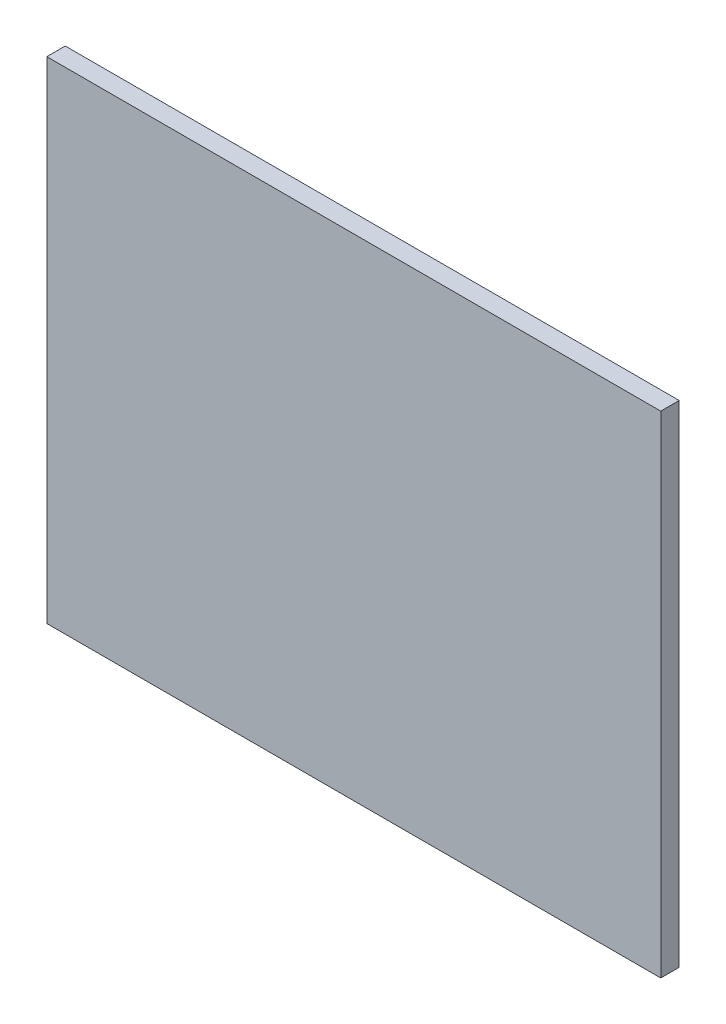
SolidWorks part; units mm, degrees
ref_plane "Přední rovina" through (0, 0, 0) normal (0, 0, 1) x (1, 0, 0)
ref_plane "Horní rovina" through (0, 0, 0) normal (0, 1, 0) x (1, 0, 0)
ref_plane "Pravá rovina" through (0, 0, 0) normal (1, 0, 0) x (0, 0, -1)
sketch "Skica1" plane through (0, 0, 0) normal (0, 0, 1) x (1, 0, 0)
  line L1 (0, 0) -> (99.8, 0)
  line L2 (0, 0) -> (0, 79.8)
  line L3 (0, 79.8) -> (99.8, 79.8)
  line L4 (99.8, 0) -> (99.8, 79.8)
  dimension "D1" = 99.8
  dimension "D2" = 79.8
extrude "Přidat vysunutím1" add sketch "Skica1" along normal blind 3
